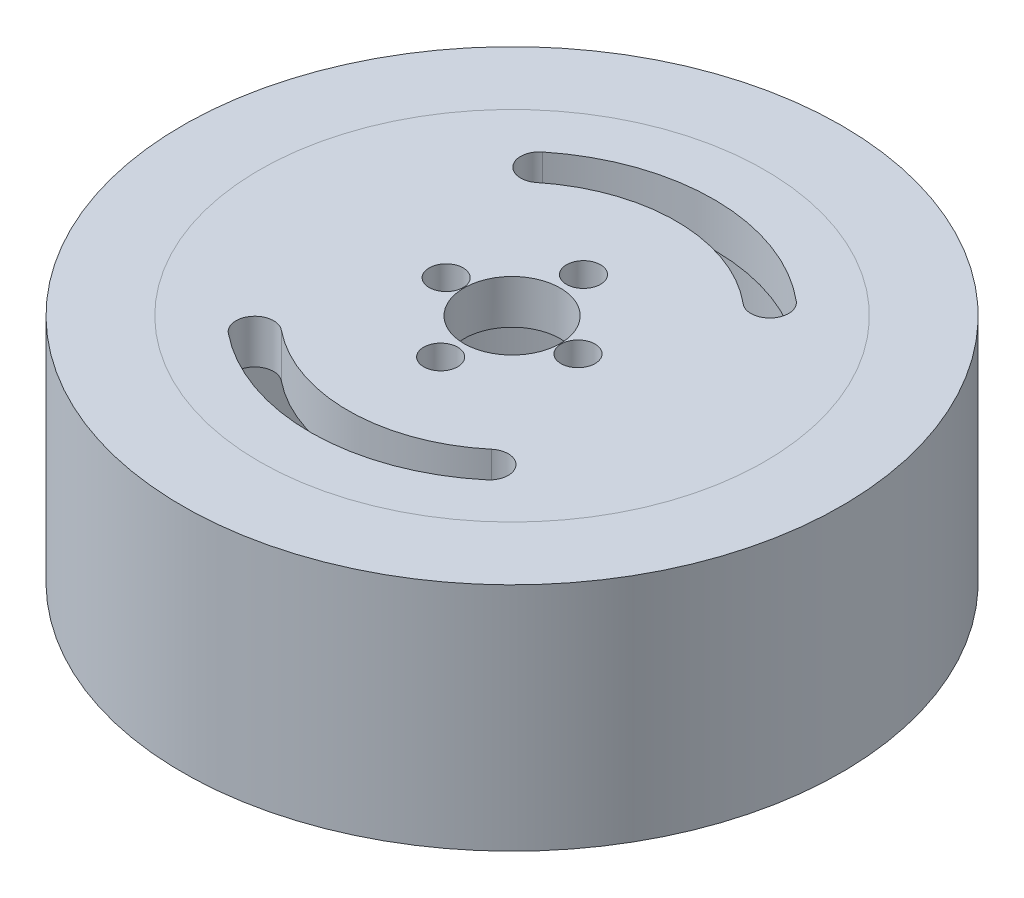
SolidWorks part; units mm, degrees
ref_plane "前视基准面" through (0, 0, 0) normal (0, 0, 1) x (1, 0, 0)
ref_plane "上视基准面" through (0, 0, 0) normal (0, 1, 0) x (1, 0, 0)
ref_plane "右视基准面" through (0, 0, 0) normal (1, 0, 0) x (0, 0, -1)
sketch "草图1" plane through (0, 0, 0) normal (0, 1, 0) x (1, 0, 0)
  circle A0 centre (0, 0) radius 30
  dimension "D1" = 60
extrude "凸台-拉伸1" add sketch "草图1" along normal blind 21
sketch "草图2" plane through (0, 0, 0) normal (0, -1, 0) x (1, 0, 0)
  circle A0 centre (0, 0) radius 21
  circle A2 centre (0, 0) radius 30 construction
  dimension "D1" = 42
  dimension "D2" = 9
extrude "切除-拉伸1" cut sketch "草图2" against normal blind 17
sketch "草图3" plane through (0, 0, 0) normal (0, -1, 0) x (1, 0, 0)
  circle A3 centre (0, 0) radius 23
  circle A4 centre (0, 0) radius 23
  dimension "D1" = 2
split line "分割线1"
sketch "草图4" plane through (0, 21, 0) normal (0, 1, 0) x (1, 0, 0)
  line L0 (-6, 0) -> (6, 0) construction
  line L1 (0, 6.5) -> (0, -6.5) construction
  line L2 (0.1516, 16.6523) -> (0, 0) construction
  line L3 (-10.4627, 12.9558) -> (0, 0) construction
  line L4 (0, 0) -> (10.6968, 12.7632) construction
  line L5 (0, 0) -> (10.6968, -12.7632) construction
  line L6 (-10.4627, -12.9558) -> (0, 0) construction
  line L7 (0.1516, -16.6523) -> (0, 0) construction
  circle A0 centre (-6, 0) radius 1.55
  circle A1 centre (0, 6.5) radius 1.55
  circle A2 centre (6, 0) radius 1.55
  circle A3 centre (0, -6.5) radius 1.55
  circle A4 centre (0, 0) radius 4.3845
  arc A5 (-10.4627, 12.9558) -> (10.6968, 12.7632) centre (0, 0) cw construction
  arc A6 (11.7982, 14.0773) -> (-11.54, 14.2897) centre (0, 0) ccw
  arc A7 (9.5955, 11.4491) -> (-9.3855, 11.6219) centre (0, 0) ccw
  arc A8 (9.5955, 11.4491) -> (11.7982, 14.0773) centre (10.6968, 12.7632) ccw
  arc A9 (-11.54, 14.2897) -> (-9.3855, 11.6219) centre (-10.4627, 12.9558) ccw
  arc A10 (-10.4627, -12.9558) -> (10.6968, -12.7632) centre (0, 0) ccw construction
  arc A11 (11.7982, -14.0773) -> (-11.54, -14.2897) centre (0, 0) cw
  arc A12 (9.5955, -11.4491) -> (-9.3855, -11.6219) centre (0, 0) cw
  arc A13 (9.5955, -11.4491) -> (11.7982, -14.0773) centre (10.6968, -12.7632) cw
  arc A14 (-11.54, -14.2897) -> (-9.3855, -11.6219) centre (-10.4627, -12.9558) cw
  point P4 (0, 0)
  point P8 (0, 0)
  point P15 (0.1516, 16.6523)
  point P26 (0.1516, -16.6523)
  dimension "D3" = 3.1
  dimension "D1" = 12
  dimension "D2" = 13
extrude "切除-拉伸3" cut sketch "草图4" against normal blind 17
